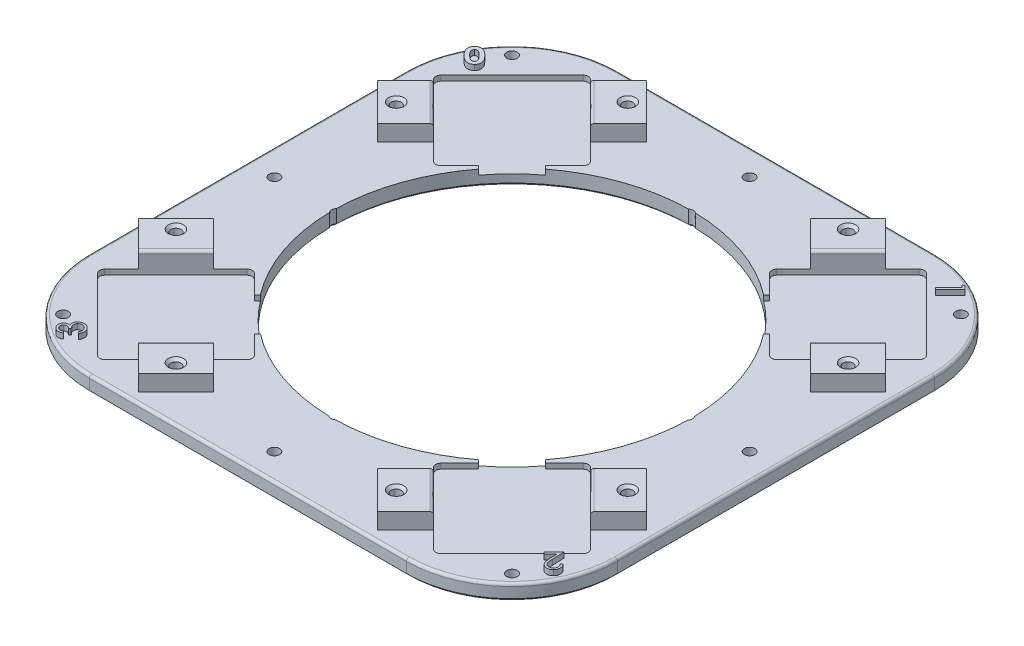
SolidWorks part; units mm, degrees
ref_plane "Спереди" through (0, 0, 0) normal (0, 0, 1) x (1, 0, 0)
ref_plane "Сверху" through (0, 0, 0) normal (0, 1, 0) x (1, 0, 0)
ref_plane "Справа" through (0, 0, 0) normal (1, 0, 0) x (0, 0, -1)
sketch "Эскиз1" plane through (0, 0, 0) normal (0, 1, 0) x (1, 0, 0)
  line L1 (-100, -100) -> (100, -100)
  line L2 (-100, -100) -> (-100, 100)
  line L3 (-100, 100) -> (100, 100)
  line L4 (100, -100) -> (100, 100)
  line L5 (0, 100) -> (0, -100) construction
  line L6 (-100, 0) -> (100, 0) construction
  line L11 (0, 75) -> (0, -75) construction
  line L12 (-39.5, 0) -> (39.5, 0) construction
  line L13 (-85, -85) -> (85, -85) construction
  line L14 (-85, -85) -> (-85, 85) construction
  line L15 (-85, 85) -> (85, 85) construction
  line L16 (85, -85) -> (85, 85) construction
  line L17 (0, 85) -> (0, -85) construction
  line L18 (-85, 0) -> (85, 0) construction
  circle A8 centre (-90, 0) radius 2
  circle A9 centre (0, 90) radius 2
  circle A10 centre (90, 0) radius 2
  circle A11 centre (0, -90) radius 2
  circle A12 centre (-85, 85) radius 2
  circle A13 centre (85, 85) radius 2
  circle A14 centre (85, -85) radius 2
  circle A15 centre (-85, -85) radius 2
  point P0 (0, 0)
  point P4 (0, 0)
  point P11 (0, 0)
  point P27 (0, 0)
  dimension "D6" = 90
  dimension "D1" = 200
  dimension "D8" = 170
  dimension "D7" = 4
extrude "Бобышка-Вытянуть1" add sketch "Эскиз1" along normal blind 6
sketch "Эскиз2" plane through (0, 6, 0) normal (0, 1, 0) x (1, 0, 0)
  line L0 (0, 72.2532) -> (0, 0) construction
  line L1 (0, 0) -> (100, 100) construction
  line L2 (63.6396, 33.9411) -> (33.9411, 63.6396)
  line L3 (63.6396, 33.9411) -> (93.3381, 63.6396)
  line L4 (33.9411, 63.6396) -> (63.6396, 93.3381)
  line L5 (93.3381, 63.6396) -> (63.6396, 93.3381)
  line L6 (63.6396, 33.9411) -> (63.6396, 93.3381) construction
  line L7 (33.9411, 63.6396) -> (93.3381, 63.6396) construction
  line L8 (33.9411, -63.6396) -> (63.6396, -33.9411)
  line L9 (33.9411, -63.6396) -> (63.6396, -93.3381)
  line L10 (63.6396, -93.3381) -> (93.3381, -63.6396)
  line L11 (63.6396, -33.9411) -> (93.3381, -63.6396)
  line L12 (-63.6396, -33.9411) -> (-33.9411, -63.6396)
  line L13 (-63.6396, -33.9411) -> (-93.3381, -63.6396)
  line L14 (-93.3381, -63.6396) -> (-63.6396, -93.3381)
  line L15 (-33.9411, -63.6396) -> (-63.6396, -93.3381)
  line L16 (-33.9411, 63.6396) -> (-63.6396, 33.9411)
  line L17 (-33.9411, 63.6396) -> (-63.6396, 93.3381)
  line L18 (-63.6396, 93.3381) -> (-93.3381, 63.6396)
  line L19 (-63.6396, 33.9411) -> (-93.3381, 63.6396)
  line L20 (0, 0) -> (119.0497, 0) construction
  point P6 (63.6396, 63.6396)
  point P24 (0, 0)
  dimension "D1" = 42
  dimension "D2" = 90
  dimension "D4" = 63.6396
  dimension "D5" = 63.6396
  dimension "D3" = 4
extrude "Вырез-Вытянуть1" cut sketch "Эскиз2" against normal blind 2
fillet "Скругление1" radius 2 16 edges at (63.6396, 5, -33.9411) (33.9411, 5, -63.6396) (93.3381, 5, -63.6396) (63.6396, 5, -93.3381) (-63.6396, 5, -93.3381) (-63.6396, 5, -33.9411) (-93.3381, 5, -63.6396) (-33.9411, 5, -63.6396) (63.6396, 5, 93.3381) (93.3381, 5, 63.6396) (63.6396, 5, 33.9411) (33.9411, 5, 63.6396) (-63.6396, 5, 93.3381) (-33.9411, 5, 63.6396) (-63.6396, 5, 33.9411) (-93.3381, 5, 63.6396)
sketch "Эскиз3" plane through (0, 6, 0) normal (0, 1, 0) x (1, 0, 0)
  line L0 (48.7904, 48.7904) -> (67.3817, 67.3817) construction
  line L1 (35.3553, 62.2254) -> (62.2254, 35.3553) construction
  line L2 (48.7904, 78.4889) -> (78.4889, 48.7904) construction
  line L3 (62.2254, 91.9239) -> (35.3553, 65.0538) construction
  line L4 (65.0538, 35.3553) -> (91.9239, 62.2254) construction
  line L5 (41.7193, 71.4178) -> (55.8614, 85.5599)
  line L6 (41.7193, 71.4178) -> (31.1127, 82.0244)
  line L7 (55.8614, 85.5599) -> (45.2548, 96.1665)
  line L8 (31.1127, 82.0244) -> (45.2548, 96.1665)
  line L9 (62.2254, 91.9239) -> (35.3553, 65.0538) construction
  line L10 (85.5599, 55.8614) -> (96.1665, 45.2548)
  line L11 (82.0244, 31.1127) -> (96.1665, 45.2548)
  line L12 (71.4178, 41.7193) -> (82.0244, 31.1127)
  line L13 (71.4178, 41.7193) -> (85.5599, 55.8614)
  line L44 (65.0538, 35.3553) -> (91.9239, 62.2254) construction
  line L45 (0, 128.3294) -> (0, 0) construction
  line L64 (0, 0) -> (145.1139, 0) construction
  line L65 (62.2254, 91.9239) -> (35.3553, 65.0538) construction
  line L90 (48.7904, -78.4889) -> (78.4889, -48.7904) construction
  line L91 (48.7904, -48.7904) -> (67.3817, -67.3817) construction
  line L92 (71.4178, -41.7193) -> (85.5599, -55.8614)
  line L93 (71.4178, -41.7193) -> (82.0244, -31.1127)
  line L94 (82.0244, -31.1127) -> (96.1665, -45.2548)
  line L95 (85.5599, -55.8614) -> (96.1665, -45.2548)
  line L96 (31.1127, -82.0244) -> (45.2548, -96.1665)
  line L97 (55.8614, -85.5599) -> (45.2548, -96.1665)
  line L98 (41.7193, -71.4178) -> (31.1127, -82.0244)
  line L99 (41.7193, -71.4178) -> (55.8614, -85.5599)
  line L100 (-48.7904, -48.7904) -> (-67.3817, -67.3817) construction
  line L101 (-48.7904, -78.4889) -> (-78.4889, -48.7904) construction
  line L102 (-48.7904, 78.4889) -> (-78.4889, 48.7904) construction
  line L103 (-48.7904, 48.7904) -> (-67.3817, 67.3817) construction
  line L104 (-41.7193, -71.4178) -> (-55.8614, -85.5599)
  line L105 (-41.7193, -71.4178) -> (-31.1127, -82.0244)
  line L106 (-55.8614, -85.5599) -> (-45.2548, -96.1665)
  line L107 (-31.1127, -82.0244) -> (-45.2548, -96.1665)
  line L108 (-85.5599, -55.8614) -> (-96.1665, -45.2548)
  line L109 (-82.0244, -31.1127) -> (-96.1665, -45.2548)
  line L110 (-71.4178, -41.7193) -> (-82.0244, -31.1127)
  line L111 (-71.4178, -41.7193) -> (-85.5599, -55.8614)
  line L112 (-71.4178, 41.7193) -> (-85.5599, 55.8614)
  line L113 (-71.4178, 41.7193) -> (-82.0244, 31.1127)
  line L114 (-82.0244, 31.1127) -> (-96.1665, 45.2548)
  line L115 (-85.5599, 55.8614) -> (-96.1665, 45.2548)
  line L116 (-31.1127, 82.0244) -> (-45.2548, 96.1665)
  line L117 (-55.8614, 85.5599) -> (-45.2548, 96.1665)
  line L118 (-41.7193, 71.4178) -> (-31.1127, 82.0244)
  line L119 (-41.7193, 71.4178) -> (-55.8614, 85.5599)
  point P16 (48.7904, 78.4889)
  dimension "D1" = 20
  dimension "D2" = 15
extrude "Бобышка-Вытянуть3" add sketch "Эскиз3" along normal blind 6
fillet "Скругление4" radius 40 4 edges at (100, 3, -100) (100, 3, 100) (-100, 3, 100) (-100, 3, -100)
sketch "Эскиз4" plane through (0, 12, 0) normal (0, 1, 0) x (1, 0, 0)
  line L0 (89.0955, 38.1838) -> (38.1838, 89.0955) construction
  line L1 (82.0244, 31.1127) -> (96.1665, 45.2548) construction
  line L2 (45.2548, 96.1665) -> (31.1127, 82.0244) construction
  line L3 (41.7193, 71.4178) -> (55.8614, 85.5599) construction
  line L4 (48.7904, 48.7904) -> (78.4889, 78.4889) construction
  line L5 (35.3553, 62.2254) -> (62.2254, 35.3553) construction
  line L6 (91.9239, 65.0538) -> (65.0538, 91.9239) construction
  line L7 (0, 119.2498) -> (0, 0) construction
  line L8 (0, 0) -> (156.895, 0) construction
  line L9 (48.7904, -48.7904) -> (78.4889, -78.4889) construction
  line L10 (89.0955, -38.1838) -> (38.1838, -89.0955) construction
  line L11 (-89.0955, -38.1838) -> (-38.1838, -89.0955) construction
  line L12 (-48.7904, -48.7904) -> (-78.4889, -78.4889) construction
  line L13 (-48.7904, 48.7904) -> (-78.4889, 78.4889) construction
  line L14 (-89.0955, 38.1838) -> (-38.1838, 89.0955) construction
  circle A0 centre (41.7193, 85.5599) radius 1.9
  circle A1 centre (85.5599, 41.7193) radius 1.9
  circle A14 centre (85.5599, -41.7193) radius 1.9
  circle A15 centre (41.7193, -85.5599) radius 1.9
  circle A16 centre (-41.7193, -85.5599) radius 1.9
  circle A17 centre (-85.5599, -41.7193) radius 1.9
  circle A18 centre (-85.5599, 41.7193) radius 1.9
  circle A19 centre (-41.7193, 85.5599) radius 1.9
  dimension "D1" = 10
  dimension "D3" = 62
  dimension "D2" = 3.8
  dimension "D4" = 31
extrude "Вырез-Вытянуть2" cut sketch "Эскиз4" against normal blind 8
sketch "Эскиз7" plane through (0, 6, 0) normal (0, 1, 0) x (1, 0, 0)
  line L0 (0, 76.3028) -> (0, 0) construction
  line L1 (0, 0) -> (74.3797, 74.3797) construction
  line L2 (20, 6) -> (60, 6)
  line L3 (-6, 20) -> (6, 20)
  line L4 (-6, 20) -> (-6, 60)
  line L5 (-6, 60) -> (6, 60)
  line L6 (6, 20) -> (6, 60)
  line L7 (0, 60) -> (0, 20) construction
  line L8 (-6, 40) -> (6, 40) construction
  line L9 (20, 6) -> (20, -6)
  line L10 (20, -6) -> (60, -6)
  line L11 (60, 6) -> (60, -6)
  line L12 (6, -20) -> (6, -60)
  line L13 (6, -20) -> (-6, -20)
  line L14 (-6, -20) -> (-6, -60)
  line L15 (6, -60) -> (-6, -60)
  line L16 (-20, -6) -> (-60, -6)
  line L17 (-20, -6) -> (-20, 6)
  line L18 (-20, 6) -> (-60, 6)
  line L19 (-60, -6) -> (-60, 6)
  circle A0 centre (28.2843, 28.2843) radius 12
  circle A1 centre (28.2843, -28.2843) radius 12
  circle A2 centre (-28.2843, -28.2843) radius 12
  circle A3 centre (-28.2843, 28.2843) radius 12
  point P6 (0, 40)
  point P15 (0, 0)
  point P32 (0, 0)
  dimension "D1" = 40
  dimension "D2" = 24
  dimension "D4" = 12
  dimension "D5" = 40
  dimension "D6" = 40
  dimension "D3" = 4
  dimension "D7" = 4
extrude "Вырез-Вытянуть3" cut sketch "Эскиз7" against normal blind 6
sketch "Эскиз8" plane through (0, 6, 0) normal (0, 1, 0) x (1, 0, 0)
  line L0 (48.7904, 48.7904) -> (72.3205, 72.3205) construction
  line L1 (35.3553, 62.2254) -> (62.2254, 35.3553) construction
  line L2 (44.5477, 31.8198) -> (31.8198, 44.5477)
  line L3 (44.5477, 31.8198) -> (65.7609, 53.033)
  line L4 (31.8198, 44.5477) -> (53.033, 65.7609)
  line L5 (65.7609, 53.033) -> (53.033, 65.7609)
  line L6 (44.5477, 31.8198) -> (53.033, 65.7609) construction
  line L7 (31.8198, 44.5477) -> (65.7609, 53.033) construction
  line L20 (0, 107.5006) -> (0, 0) construction
  line L21 (0, 0) -> (140.6034, 0) construction
  line L22 (31.8198, -44.5477) -> (65.7609, -53.033) construction
  line L23 (44.5477, -31.8198) -> (53.033, -65.7609) construction
  line L24 (48.7904, -48.7904) -> (72.3205, -72.3205) construction
  line L25 (65.7609, -53.033) -> (53.033, -65.7609)
  line L26 (31.8198, -44.5477) -> (53.033, -65.7609)
  line L27 (44.5477, -31.8198) -> (65.7609, -53.033)
  line L28 (44.5477, -31.8198) -> (31.8198, -44.5477)
  line L29 (-48.7904, -48.7904) -> (-72.3205, -72.3205) construction
  line L30 (-44.5477, -31.8198) -> (-53.033, -65.7609) construction
  line L31 (-31.8198, -44.5477) -> (-65.7609, -53.033) construction
  line L32 (-31.8198, 44.5477) -> (-65.7609, 53.033) construction
  line L33 (-44.5477, 31.8198) -> (-53.033, 65.7609) construction
  line L34 (-48.7904, 48.7904) -> (-72.3205, 72.3205) construction
  line L35 (-44.5477, -31.8198) -> (-31.8198, -44.5477)
  line L36 (-44.5477, -31.8198) -> (-65.7609, -53.033)
  line L37 (-31.8198, -44.5477) -> (-53.033, -65.7609)
  line L38 (-65.7609, -53.033) -> (-53.033, -65.7609)
  line L39 (-65.7609, 53.033) -> (-53.033, 65.7609)
  line L40 (-31.8198, 44.5477) -> (-53.033, 65.7609)
  line L41 (-44.5477, 31.8198) -> (-65.7609, 53.033)
  line L42 (-44.5477, 31.8198) -> (-31.8198, 44.5477)
  point P24 (0, 16.9706)
  dimension "D1" = 18
  dimension "D2" = 30
extrude "Вырез-Вытянуть4" cut sketch "Эскиз8" against normal blind 2 contours L2 L3 L5 L4
fillet "Скругление6" radius 1 8 edges at (78.4889, 12, -48.7904) (48.7904, 12, -78.4889) (-78.4889, 12, 48.7904) (-48.7904, 12, 78.4889) (48.7904, 12, 78.4889) (78.4889, 12, 48.7904) (-78.4889, 12, -48.7904) (-48.7904, 12, -78.4889)
sketch "Эскиз9" plane through (0, 6, 0) normal (0, 1, 0) x (1, 0, 0)
  line L0 (-70.7105, 0.151) -> (0.151, 70.7105) construction
  line L1 (-70.7105, 0.151) -> (-0.151, -70.7105) construction
  line L2 (0.151, 70.7105) -> (70.7105, -0.151) construction
  line L3 (-0.151, -70.7105) -> (70.7105, -0.151) construction
  line L4 (-70.7105, 0.151) -> (70.7105, -0.151) construction
  line L5 (0.151, 70.7105) -> (-0.151, -70.7105) construction
  line L6 (0, 0) -> (60.8554, 60.8554) construction
  circle A0 centre (0.1419, 66.4679) radius 2
  circle A4 centre (-0.1419, -66.4679) radius 2
  circle A5 centre (66.4679, -0.1419) radius 2
  circle A6 centre (-66.4679, 0.1419) radius 2
  point P1 (0, 0)
  dimension "D2" = 4
  dimension "D3" = 3
  dimension "D4" = 3
  dimension "D5" = 94
  dimension "D1" = 100
extrude "Вырез-Вытянуть5" cut sketch "Эскиз9" against normal blind 10
sketch "Эскиз10" plane through (0, 6, 0) normal (0, 1, 0) x (1, 0, 0)
  line L0 (-89.4334, 70.8427) -> (-83.9454, 76.3307) construction
  line L1 (0, 108.5259) -> (0, 0) construction
  line L2 (71.3984, 88.9173) -> (76.8147, 83.501) construction
  line L3 (90.0364, -69.9365) -> (84.274, -75.6989) construction
  line L4 (-72.0522, -89.0668) -> (-79.6906, -81.6618) construction
  text T0 "<b>0</b>\r\n" font "Century Gothic" height 8
  text T1 "1\r\n" font "Century Gothic" height 8
  text T2 "2" font "Century Gothic" height 8
  text T3 "3\r\n" font "Century Gothic" height 8
extrude "Бобышка-Вытянуть6" add sketch "Эскиз10" along normal blind 2
fillet "Скругление9" radius 1 8 edges at (88.2843, 6, 88.2843) (0, 6, 100) (-88.2843, 6, 88.2843) (-100, 6, 0) (-88.2843, 6, -88.2843) (0, 6, -100) (88.2843, 6, -88.2843) (100, 6, 0)
sketch "Эскиз11" plane through (0, 6, 0) normal (0, 1, 0) x (1, 0, 0)
  circle A0 centre (0, 0) radius 68
  dimension "D1" = 136
extrude "Вырез-Вытянуть6" cut sketch "Эскиз11" against normal through all both and the other way through all
chamfer "Фаска1" distance 1 angle 45 24 edges at (100, 0, 0) (88.2843, 0, -88.2843) (88.2843, 0, 88.2843) (0, 0, -100) (0, 0, 100) (-88.2843, 0, -88.2843) (-88.2843, 0, 88.2843) (-100, 0, 0) (-85, 0, 87) (85, 0, -83) (-90, 0, 2) (90, 0, 2) (0, 0, -88) (0, 0, 92) (-85, 0, -83) (85, 0, 87) (-68.4679, 0, -0.1462) (68.4679, 0, 0.1462) (-0.1462, 0, 68.4679) (0.1462, 0, -68.4679) (47.9805, 0, 48.1858) (-48.1858, 0, 47.9805) (-47.9805, 0, -48.1858) (48.1858, 0, -47.9805)
chamfer "Фаска2" distance 1 angle 45 8 edges at (-85.5599, 12, 39.8193) (-41.7193, 12, 87.4599) (41.7193, 12, 83.6599) (85.5599, 12, 43.6193) (85.5599, 12, -43.6193) (41.7193, 12, -83.6599) (-85.5599, 12, -39.8193) (-41.7193, 12, -87.4599)
